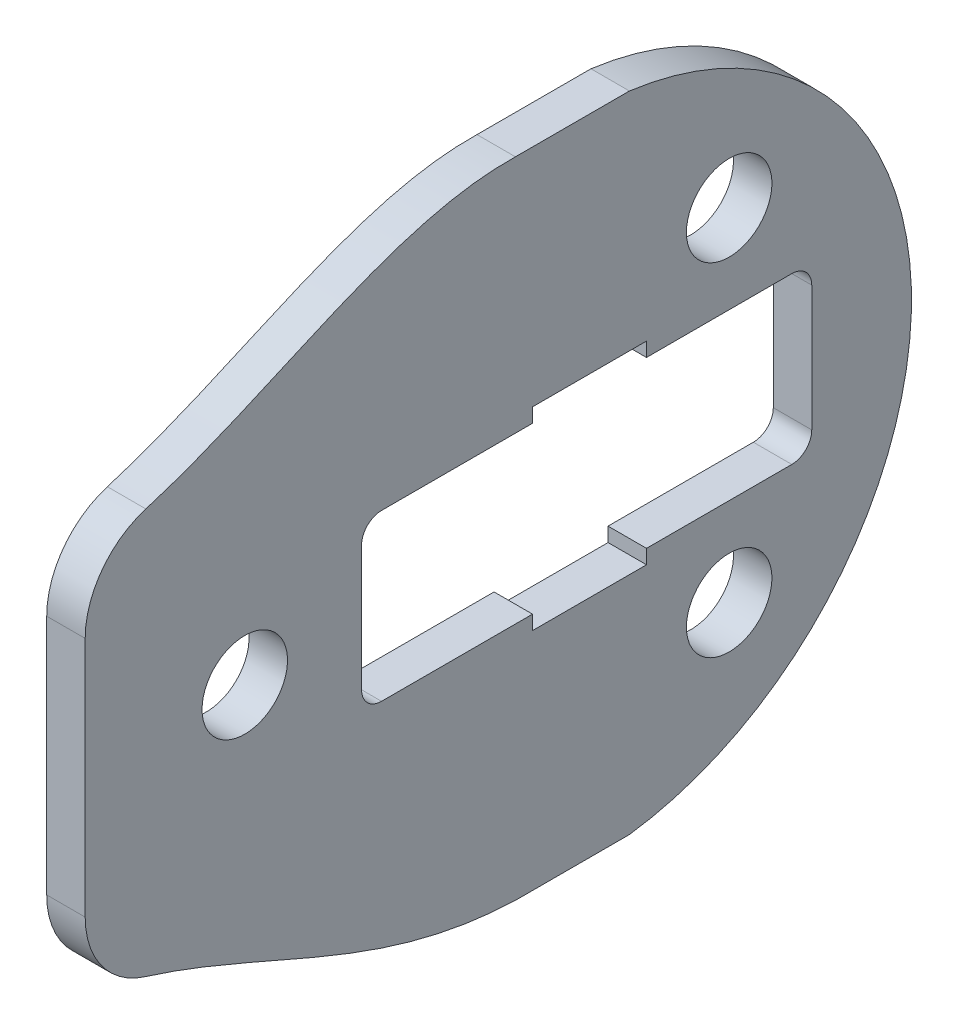
SolidWorks part; units mm, degrees
ref_plane "Piano frontale" through (0, 0, 0) normal (0, 0, 1) x (1, 0, 0)
ref_plane "Piano superiore" through (0, 0, 0) normal (0, 1, 0) x (1, 0, 0)
ref_plane "Piano destro" through (0, 0, 0) normal (1, 0, 0) x (0, 0, -1)
sketch "Schizzo1" plane through (0, 0, 0) normal (1, 0, 0) x (0, 0, -1)
  line L4 (-2.501, -10.3) -> (-2.501, -11.3)
  line L5 (-2.501, -11.3) -> (1.499, -11.3)
  line L7 (1.499, 11.3) -> (-2.501, 11.3)
  line L8 (-2.501, 11.3) -> (-2.501, 10.3)
  line L15 (0, 0) -> (-20.601, 0)
  line L16 (3.245, -2.9) -> (7.899, -2.9)
  line L17 (-7.9, 2.9) -> (2.1, 2.9)
  line L20 (-7.9, 2.9) -> (-7.9, -2.9)
  line L21 (-7.9, -2.9) -> (3.245, -2.9)
  line L30 (-2.501, 10.3) -> (-7.501, 10.3)
  line L31 (-7.501, 10.3) -> (-7.501, 6.3)
  line L35 (-20.601, 6.3) -> (-20.601, -6.3)
  line L37 (-7.501, -6.3) -> (-7.501, -10.3)
  line L38 (-7.501, -10.3) -> (-2.501, -10.3)
  line L40 (7.899, -2.9) -> (7.899, 2.9)
  line L41 (7.899, 2.9) -> (2.1, 2.9)
  line L43 (-1.901, -2.9) -> (2.099, -2.9)
  line L47 (-1.901, -2.9) -> (-1.901, -3.4)
  line L48 (-1.901, -3.4) -> (2.099, -3.4)
  line L49 (2.099, -2.9) -> (2.099, -3.4)
  line L50 (-1.901, 2.9) -> (2.099, 2.9)
  line L51 (-1.901, 2.9) -> (-1.901, 3.4)
  line L52 (-17.601, 6.5611) -> (-17.601, -6.594)
  line L53 (-1.901, 3.4) -> (2.099, 3.4)
  line L54 (2.099, 2.9) -> (2.099, 3.4)
  arc A14 (1.499, 11.3) -> (1.499, -11.3) centre (0, 0) cw
  circle A19 centre (-12, 0) radius 1.5
  circle A20 centre (5, 6) radius 1.5
  circle A21 centre (5, -6) radius 1.5
  spline S0 degree 3 poles (-2.501, 11.3) (-8.3138, 11.4296) (-13.3518, 6.2167) (-20.601, 6.3) knots 0 0 0 0 1 1 1 1
  spline S1 degree 3 poles (-2.501, -11.3) (-9.1647, -11.0636) (-13.4327, -6.3399) (-20.601, -6.3) knots 0 0 0 0 1 1 1 1
  point P7 (-7.9, 0)
  point P17 (11.399, 0)
  point P41 (-20.601, 0)
  dimension "D7" = 11.399
  dimension "D12" = 3.5
  dimension "D14" = 5.8
  dimension "D15" = 0.5
  dimension "D16" = 3
  dimension "D17" = 3
  dimension "D18" = 3
  dimension "D19" = 0.5
  dimension "D22" = 6
  dimension "D1" = 32
  dimension "D2" = 22.6
  dimension "D3" = 11.3
  dimension "D4" = 1
  dimension "D5" = 1
  dimension "D6" = 4
  dimension "D8" = 5.8
  dimension "D9" = 5
  dimension "D10" = 3
  dimension "D11" = 12.6
  dimension "D13" = 10
  dimension "D20" = 4
  dimension "D21" = 7.9
  dimension "D23" = 6
  dimension "D24" = 12
  dimension "D25" = 5
extrude "Estrusione-Estrusione1" add sketch "Schizzo1" along normal blind 1.35
fillet "Raccordo2" radius 3 1 edges at (0.675, -6.594, 17.601)
fillet "Raccordo3" radius 3 1 edges at (0.675, 6.5611, 17.601)
fillet "Raccordo4" radius 0.7 4 edges at (0.675, 2.9, -7.899) (0.675, -2.9, -7.899) (0.675, -2.9, 7.9) (0.675, 2.9, 7.9)
